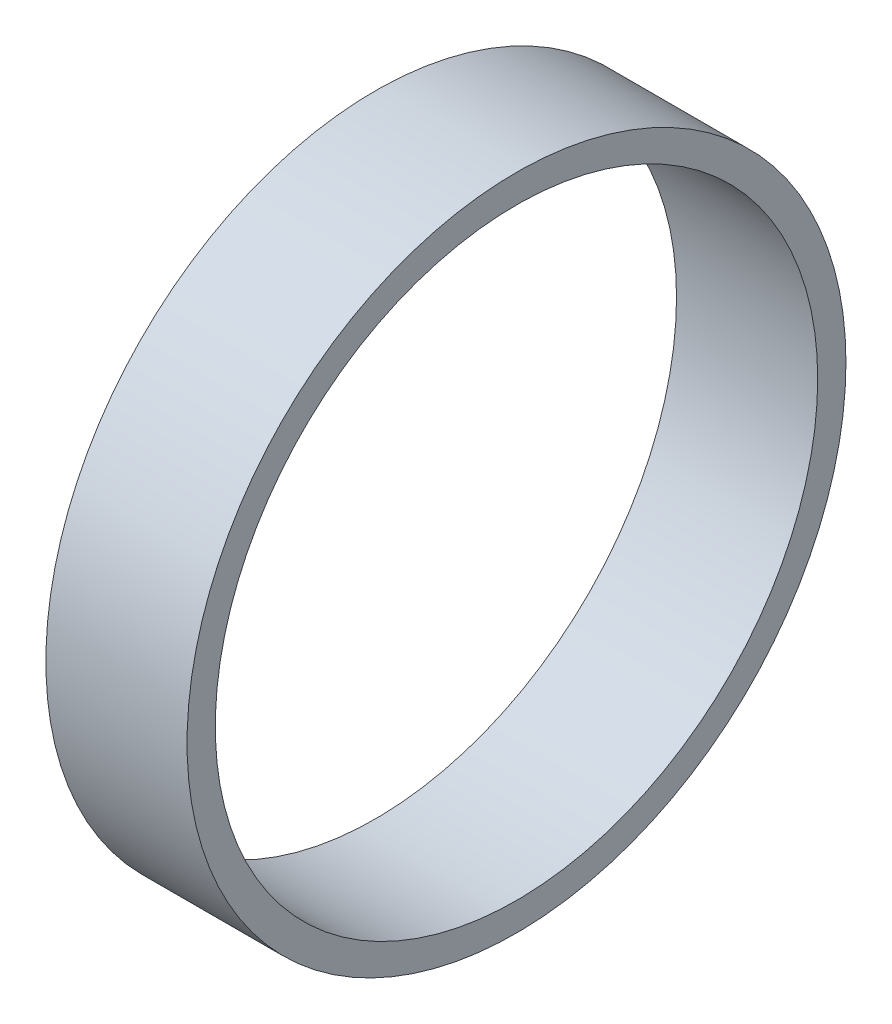
SolidWorks part; units mm, degrees
ref_plane "Front Plane" through (0, 0, 0) normal (0, 0, 1) x (1, 0, 0)
ref_plane "Top Plane" through (0, 0, 0) normal (0, 1, 0) x (1, 0, 0)
ref_plane "Right Plane" through (0, 0, 0) normal (1, 0, 0) x (0, 0, -1)
sketch "Sketch1" plane through (0, 0, 0) normal (1, 0, 0) x (0, 0, -1)
  circle A0 centre (0, 0) radius 32
  circle A1 centre (0, 0) radius 35
  dimension "D1" = 64
  dimension "D2" = 70
extrude "Boss-Extrude1" add sketch "Sketch1" along normal blind 15
